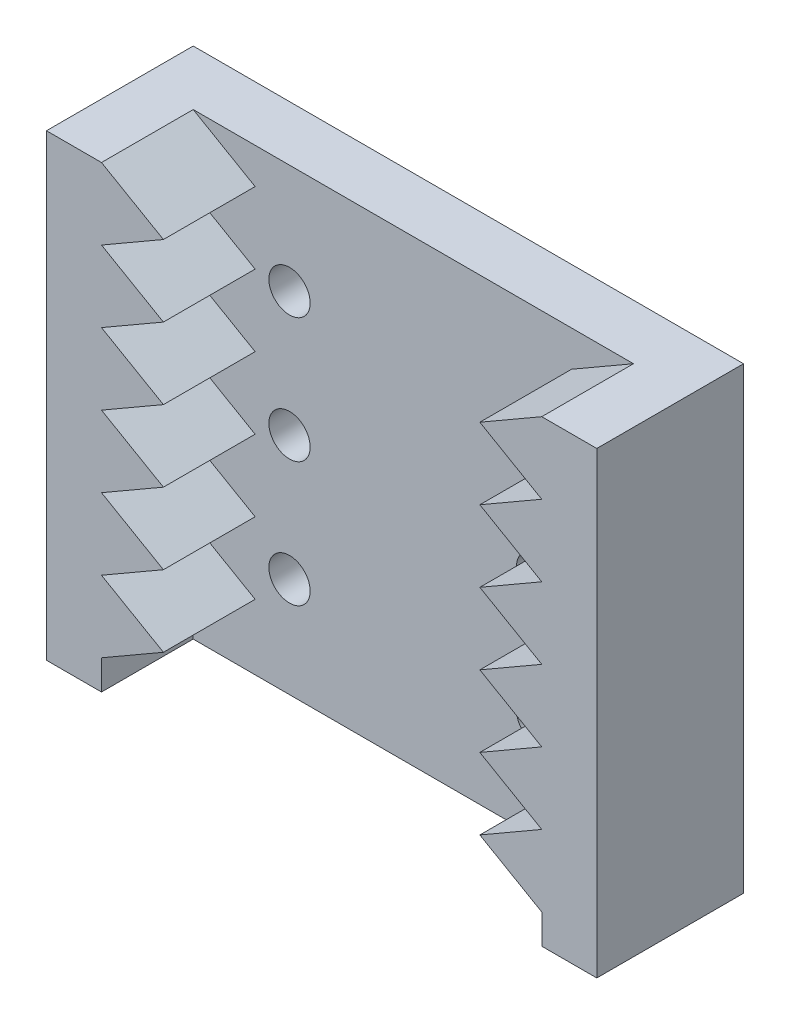
SolidWorks part; units mm, degrees
ref_plane "Front Plane" through (0, 0, 0) normal (0, 0, 1) x (1, 0, 0)
ref_plane "Top Plane" through (0, 0, 0) normal (0, 1, 0) x (1, 0, 0)
ref_plane "Right Plane" through (0, 0, 0) normal (1, 0, 0) x (0, 0, -1)
sketch "Sketch1" plane through (0, 0, 0) normal (0, 0, 1) x (1, 0, 0)
  line L0 (0, 20.0918) -> (0, -16.5447) construction
  line L5 (-12, 12.5) -> (12, 12.5)
  line L6 (-12, 12.5) -> (-12, -12.5)
  line L7 (-12, -12.5) -> (12, -12.5)
  line L8 (12, 12.5) -> (12, -12.5)
  line L9 (6.75, 20.0918) -> (6.75, -16.1741) construction
  line L10 (-6.75, 20.0918) -> (-6.75, -16.1741) construction
  line L11 (-6.75, 20.0918) -> (0, 20.0918) construction
  line L12 (6.75, 20.0918) -> (0, 20.0918) construction
  line L13 (-24.4484, -7.05) -> (15.0323, -7.05) construction
  line L14 (-23.1395, -0.25) -> (15.0323, -0.25) construction
  line L15 (-20.1747, 6.55) -> (15.0323, 6.55) construction
  line L16 (15.0323, 6.55) -> (15.0323, -0.25) construction
  line L17 (15.0323, -0.25) -> (15.0323, -7.05) construction
  circle A0 centre (-6.75, 6.55) radius 1.125
  circle A1 centre (-6.75, -0.25) radius 1.125
  circle A2 centre (-6.75, -7.05) radius 1.125
  circle A3 centre (6.75, -7.05) radius 1.125
  circle A4 centre (6.75, -0.25) radius 1.125
  circle A5 centre (6.75, 6.55) radius 1.125
  point P4 (-12, 0)
  point P5 (0, -12.5)
  dimension "D6" = 2.25
  dimension "D1" = 25
  dimension "D2" = 24
  dimension "D3" = 6.75
  dimension "D4" = 5.45
  dimension "D5" = 6.8
extrude "Boss-Extrude1" add sketch "Sketch1" along normal blind 3
sketch "Sketch2" plane through (0, 0, 0) normal (0, 0, 1) x (1, 0, 0)
  line L0 (0, 15.7926) -> (0, -19.0307) construction
  line L1 (-12, 12.5) -> (-15, 12.5)
  line L2 (-15, 12.5) -> (-15, -12.5)
  line L3 (-15, -12.5) -> (-12, -12.5)
  line L4 (-7.875, 15.7926) -> (-7.875, -17.4913) construction
  line L5 (-8.625, 17.1197) -> (-8.625, -22.1627) construction
  line L6 (-12, 12.5) -> (-8.625, 10.5514)
  line L7 (-8.625, 10.5514) -> (-12, 8.6029)
  line L8 (-12, 12.5) -> (-12, -12.5) construction
  line L9 (-12, 8.6029) -> (-12, 12.5) construction
  line L10 (-12, 8.6029) -> (-8.625, 6.6543)
  line L11 (-8.625, 6.6543) -> (-12, 4.7058)
  line L12 (-12, 4.7058) -> (-8.625, 2.7572)
  line L13 (-8.625, 2.7572) -> (-12, 0.8087)
  line L14 (-12, 0.8087) -> (-8.625, -1.1399)
  line L15 (-8.625, -1.1399) -> (-12, -3.0885)
  line L16 (-12, -3.0885) -> (-8.625, -5.037)
  line L17 (-8.625, -5.037) -> (-12, -6.9856)
  line L18 (-12, -6.9856) -> (-8.625, -8.9341)
  line L19 (-8.625, -8.9341) -> (-12, -10.8827)
  line L20 (-12, -10.8827) -> (-12, -12.5)
  line L21 (12, -3.0885) -> (8.625, -5.037)
  line L22 (8.625, -1.1399) -> (12, -3.0885)
  line L23 (12, 0.8087) -> (8.625, -1.1399)
  line L24 (8.625, 2.7572) -> (12, 0.8087)
  line L25 (12, 4.7058) -> (8.625, 2.7572)
  line L26 (8.625, 6.6543) -> (12, 4.7058)
  line L27 (12, 8.6029) -> (8.625, 6.6543)
  line L28 (8.625, 10.5514) -> (12, 8.6029)
  line L29 (12, 12.5) -> (8.625, 10.5514)
  line L30 (12, 12.5) -> (15, 12.5)
  line L31 (15, 12.5) -> (15, -12.5)
  line L32 (15, -12.5) -> (12, -12.5)
  line L33 (12, -10.8827) -> (12, -12.5)
  line L34 (8.625, -8.9341) -> (12, -10.8827)
  line L35 (12, -6.9856) -> (8.625, -8.9341)
  line L36 (8.625, -5.037) -> (12, -6.9856)
  circle A0 centre (-6.75, -0.25) radius 1.125 construction
  dimension "D1" = 0.75
  dimension "D2" = 6
  dimension "D3" = 3
extrude "Boss-Extrude2" add sketch "Sketch2" along normal blind 8
